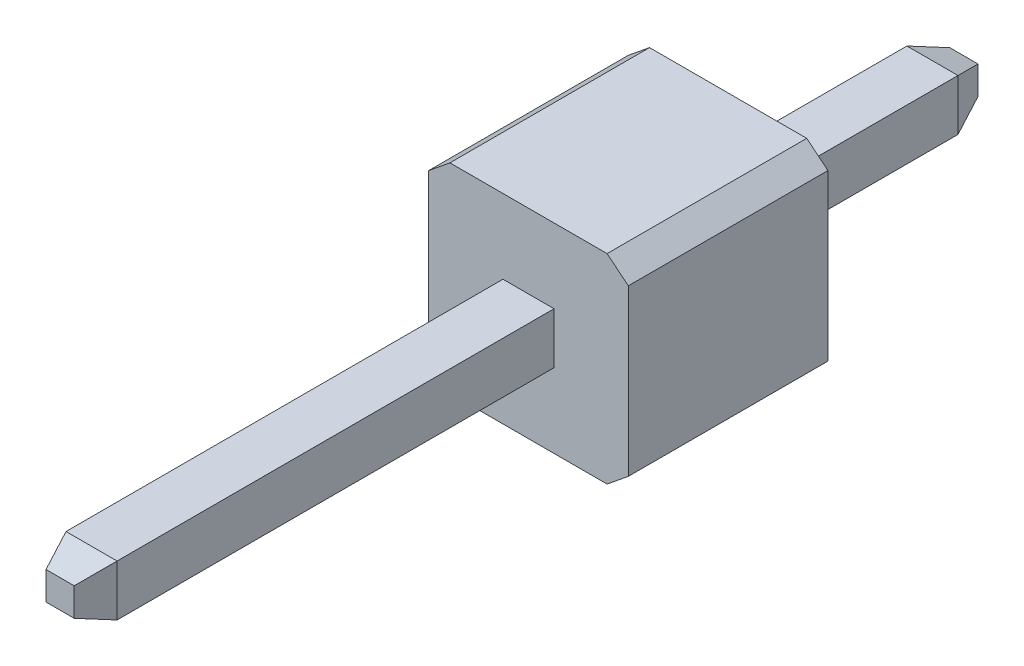
SolidWorks part; units mm, degrees
ref_plane "Front Plane" through (0, 0, 0) normal (0, 0, 1) x (1, 0, 0)
ref_plane "Top Plane" through (0, 0, 0) normal (0, 1, 0) x (1, 0, 0)
ref_plane "Right Plane" through (0, 0, 0) normal (1, 0, 0) x (0, 0, -1)
sketch "Sketch1" plane through (0, 0, 0) normal (0, 0, 1) x (1, 0, 0)
  line L1 (-0.325, 0.325) -> (0.325, 0.325)
  line L2 (-0.325, 0.325) -> (-0.325, -0.325)
  line L3 (-0.325, -0.325) -> (0.325, -0.325)
  line L4 (0.325, 0.325) -> (0.325, -0.325)
  dimension "D1" = 0.65
  dimension "D2" = 0.65
  dimension "D3" = 0.325
  dimension "D4" = 0.325
extrude "Boss-Extrude1" add sketch "Sketch1" along normal blind 11.5
chamfer "Chamfer2" distance 0.4 angle 20 4 edges at (0, 0.325, 11.5) (0.325, 0, 11.5) (0, -0.325, 11.5) (-0.325, 0, 11.5)
chamfer "Chamfer3" distance 0.4 angle 20 4 edges at (0, -0.325, 0) (0.325, 0, 0) (0, 0.325, 0) (-0.325, 0, 0)
ref_plane "Plane1" through (0, 0, 3) normal (0, 0, -1) x (-1, 0, 0)
sketch "Sketch2" plane through (0, 0, 3) normal (0, 0, -1) x (-1, 0, 0)
  line L0 (-1, 1.27) -> (1, 1.27)
  line L1 (1, 1.27) -> (1.27, 1.05)
  line L2 (1.27, 1.05) -> (1.27, -1.05)
  line L3 (1.27, -1.05) -> (1, -1.27)
  line L4 (1, -1.27) -> (-1, -1.27)
  line L5 (-1, -1.27) -> (-1.27, -1.05)
  line L6 (-1.27, -1.05) -> (-1.27, 1.05)
  line L7 (-1.27, 1.05) -> (-1, 1.27)
  line L8 (0, 0) -> (0, 1.4976) construction
  dimension "D1" = 2.1
  dimension "D2" = 2.54
  dimension "D3" = 2.54
  dimension "D4" = 1.27
  dimension "D5" = 1.27
  dimension "D6" = 2
extrude "Plastic" add sketch "Sketch2" against normal blind 2.54
